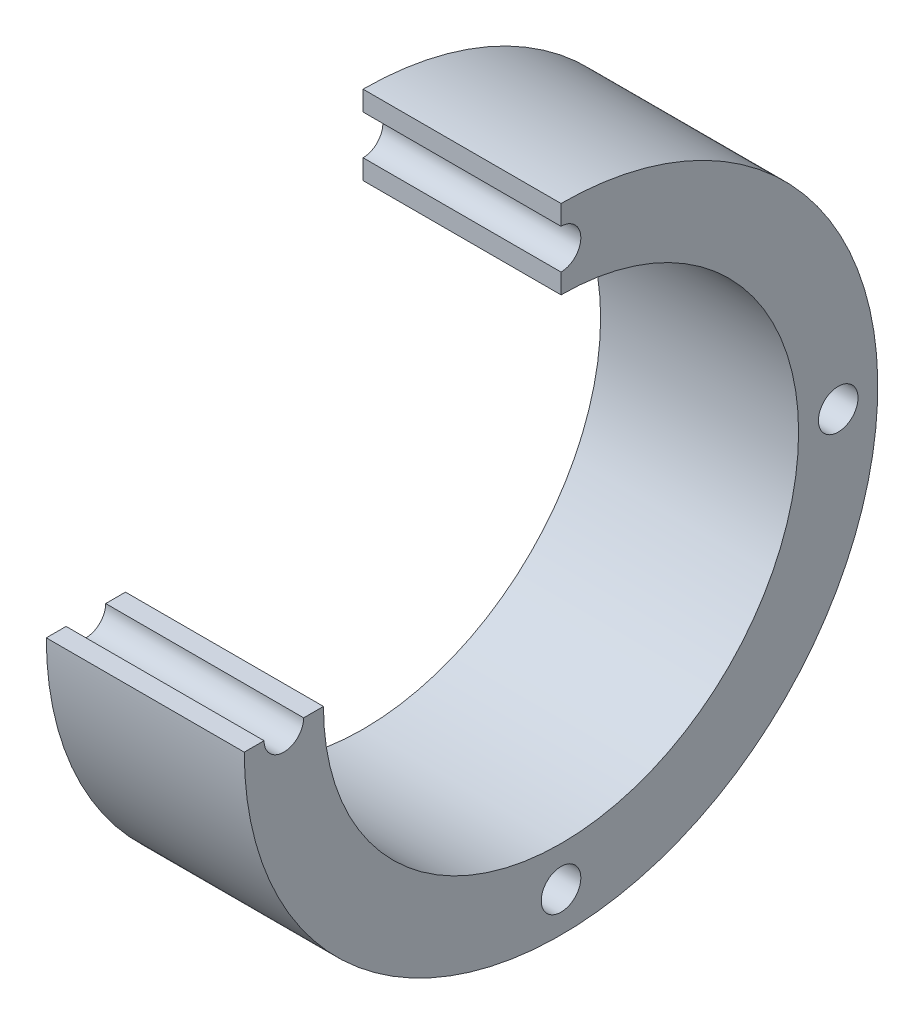
SolidWorks part; units mm, degrees
material "Copper"
ref_plane "Front Plane" through (0, 0, 0) normal (1, 0, 0) x (0, 1, 0)
ref_plane "Top Plane" through (0, 0, 0) normal (0, 0, 1) x (0, 1, 0)
ref_plane "Right Plane" through (0, 0, 0) normal (0, 1, 0) x (-1, 0, 0)
sketch "Sketch1" plane through (0, 0, 0) normal (1, 0, 0) x (0, 1, 0)
  circle A0 centre (0, 0) radius 80
  circle A2 centre (0, 0) radius 60
  dimension "D1" = 160
  dimension "D3" = 120
extrude "Boss-Extrude1" add sketch "Sketch1" along normal mid plane 50
sketch "Sketch2" plane through (25, 0, 0) normal (1, 0, 0) x (0, 1, 0)
  line L0 (0, 0) -> (-89.0293, 0) construction
  circle A0 centre (0, 0) radius 70
  circle A1 centre (-70, 0) radius 5
  dimension "D1" = 140
  dimension "D2" = 10
extrude "Cut-Extrude1" cut sketch "Sketch2" against normal through all contours A1
pattern_circular "CirPattern1" count 4 over 360 about axis through (0, 0, 0) along (1, 0, 0) of "Cut-Extrude1"
sketch "Sketch3" plane through (25, 0, 0) normal (1, 0, 0) x (0, 1, 0)
  line L0 (0, 93.4744) -> (0, 0)
  line L1 (0, 0) -> (100.6647, 0)
  line L2 (100.6647, 0) -> (100.6647, 96.5341)
  line L3 (100.6647, 96.5341) -> (0, 93.4744)
extrude "Cut-Extrude2" cut sketch "Sketch3" against normal through all
